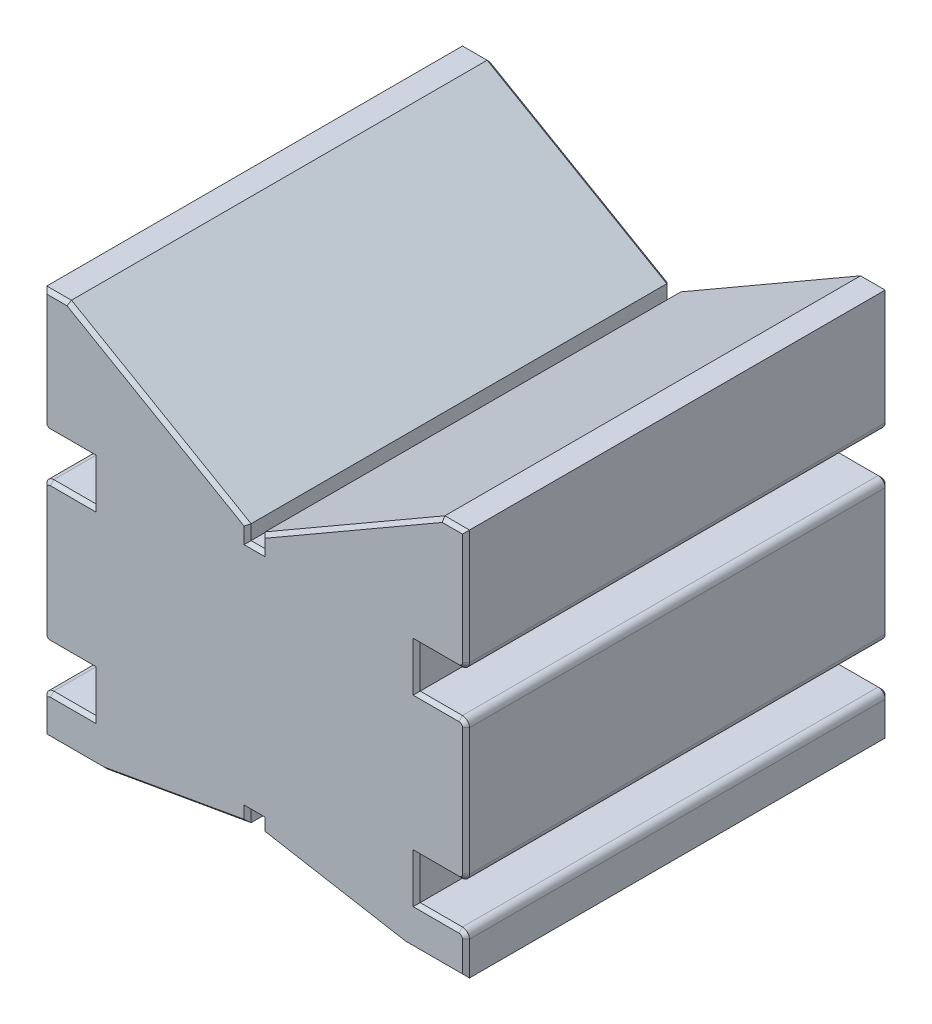
SolidWorks part; units mm, degrees
ref_plane "Front Plane" through (0, 0, 0) normal (0, 0, 1) x (1, 0, 0)
ref_plane "Top Plane" through (0, 0, 0) normal (0, 1, 0) x (1, 0, 0)
ref_plane "Right Plane" through (0, 0, 0) normal (1, 0, 0) x (0, 0, -1)
sketch "Sketch1" plane through (0, 0, 0) normal (0, 0, 1) x (1, 0, 0)
  line L0 (0, 25) -> (0, -25) construction
  line L1 (-23.3909, 0) -> (23.3909, 0) construction
  line L2 (-30, 0) -> (-30, 3)
  line L3 (-29, 4) -> (-23, 4)
  line L4 (-23, 4) -> (-23, 10)
  line L5 (-23, 10) -> (-29, 10)
  line L6 (-30, 11) -> (-30, 27.2998)
  line L7 (-30, 27.2998) -> (-26.5, 27.2998)
  line L8 (-26.5, 27.2998) -> (0, 12)
  line L9 (-30, 0) -> (-30, -15)
  line L10 (-29, -16) -> (-23, -16)
  line L11 (-23, -16) -> (-23, -22)
  line L12 (-23, -22) -> (-29, -22)
  line L13 (-30, -23) -> (-30, -27.7673)
  line L14 (-30, -27.7673) -> (-21.3656, -27.7673)
  line L15 (-21.3656, -27.7673) -> (0, -24)
  line L16 (21.3656, -27.7673) -> (0, -24)
  line L17 (30, -27.7673) -> (21.3656, -27.7673)
  line L18 (30, -23) -> (30, -27.7673)
  line L19 (23, -22) -> (29, -22)
  line L20 (23, -16) -> (23, -22)
  line L21 (29, -16) -> (23, -16)
  line L22 (30, 0) -> (30, -15)
  line L23 (26.5, 27.2998) -> (0, 12)
  line L24 (30, 27.2998) -> (26.5, 27.2998)
  line L25 (30, 11) -> (30, 27.2998)
  line L26 (23, 10) -> (29, 10)
  line L27 (23, 4) -> (23, 10)
  line L28 (29, 4) -> (23, 4)
  line L29 (30, 0) -> (30, 3)
  arc A0 (-30, -23) -> (-29, -22) centre (-29, -23) cw
  arc A1 (-30, -15) -> (-29, -16) centre (-29, -15) ccw
  arc A2 (-30, 3) -> (-29, 4) centre (-29, 3) cw
  arc A3 (-29, 10) -> (-30, 11) centre (-29, 11) cw
  arc A4 (30, -23) -> (29, -22) centre (29, -23) ccw
  arc A5 (29, -16) -> (30, -15) centre (29, -15) ccw
  arc A6 (30, 3) -> (29, 4) centre (29, 3) ccw
  arc A7 (29, 10) -> (30, 11) centre (29, 11) ccw
  point P36 (-30, -22)
  point P39 (-30, -16)
  point P42 (-30, 4)
  point P45 (-30, 10)
  point P48 (30, -22)
  point P51 (30, -16)
  point P54 (30, 4)
  point P57 (30, 10)
  dimension "D10" = 1
  dimension "D11" = 1
  dimension "D1" = 3.5
  dimension "D2" = 160
  dimension "D3" = 16
  dimension "D4" = 4
  dimension "D5" = 120
  dimension "D6" = 7
  dimension "D7" = 6
  dimension "D8" = 6
  dimension "D9" = 60
  dimension "D12" = 8
  dimension "D13" = 8
extrude "Boss-Extrude1" add sketch "Sketch1" along normal blind 60
sketch "Sketch3" plane through (0, 0, 0) normal (0, 0, -1) x (-1, 0, 0)
  line L1 (1, 10.5) -> (-1, 10.5)
  line L2 (1, 10.5) -> (1, 13.5)
  line L3 (1, 13.5) -> (-1, 13.5)
  line L4 (-1, 10.5) -> (-1, 13.5)
  line L5 (1, 10.5) -> (-1, 13.5) construction
  line L6 (1, 13.5) -> (-1, 10.5) construction
  line L7 (-1, -25.5) -> (1, -25.5)
  line L8 (-1, -25.5) -> (-1, -22.5)
  line L9 (-1, -22.5) -> (1, -22.5)
  line L10 (1, -25.5) -> (1, -22.5)
  line L11 (-1, -25.5) -> (1, -22.5) construction
  line L12 (-1, -22.5) -> (1, -25.5) construction
  point P0 (0, 12)
  point P6 (0, -24)
  dimension "D1" = 2
  dimension "D2" = 3
  dimension "D3" = 3
  dimension "D4" = 2
extrude "Cut-Extrude1" cut sketch "Sketch3" against normal through all
sketch "Sketch2" plane through (0, 0, 60) normal (0, 0, 1) x (1, 0, 0)
  line L0 (-33.9396, 80) -> (30, 80) construction
  line L1 (-29, 10) -> (-23, 10) construction
  line L2 (-30, -92) -> (29.6871, -92) construction
  line L3 (-23, -22) -> (-29, -22) construction
  point P4 (-26, 10)
  dimension "D1" = 70
  dimension "D2" = 70
chamfer "Chamfer1" distance 0.5 angle 45 80 edges at (-29.7071, 3.7071, 60) (-26, 4, 60) (-23, 7, 60) (-26, 10, 60) (-29.7071, 10.2929, 60) (-30, 19.1499, 60) (-28.25, 27.2998, 60) (-13.75, 19.9386, 60) (13.75, 19.9386, 60) (28.25, 27.2998, 60) (30, 19.1499, 60) (29.7071, 10.2929, 60) (26, 10, 60) (23, 7, 60) (26, 4, 60) (29.7071, 3.7071, 60) (30, -6, 60) (29.7071, -15.7071, 60) (26, -16, 60) (23, -19, 60) (26, -22, 60) (29.7071, -22.2929, 60) (30, -25.3837, 60) (25.6828, -27.7673, 60) (11.1828, -25.9718, 60) (-11.1828, -25.9718, 60) (-25.6828, -27.7673, 60) (-30, -25.3837, 60) (-29.7071, -22.2929, 60) (-26, -22, 60) (-23, -19, 60) (-26, -16, 60) (-29.7071, -15.7071, 60) (-30, -6, 60) (-26, -16, 0) (-23, -19, 0) (-26, -22, 0) (-29.7071, -22.2929, 0) (-30, -25.3837, 0) (-25.6828, -27.7673, 0) (-11.1828, -25.9718, 0) (11.1828, -25.9718, 0) (25.6828, -27.7673, 0) (30, -25.3837, 0) (29.7071, -22.2929, 0) (26, -22, 0) (23, -19, 0) (26, -16, 0) (29.7071, -15.7071, 0) (30, -6, 0) (29.7071, 3.7071, 0) (26, 4, 0) (23, 7, 0) (26, 10, 0) (29.7071, 10.2929, 0) (30, 19.1499, 0) (28.25, 27.2998, 0) (13.75, 19.9386, 0) (-13.75, 19.9386, 0) (-28.25, 27.2998, 0) (-30, 19.1499, 0) (-29.7071, 10.2929, 0) (-26, 10, 0) (-23, 7, 0) (-26, 4, 0) (-29.7071, 3.7071, 0) (-30, -6, 0) (-29.7071, -15.7071, 0) (1, -23.3382, 60) (0, -22.5, 60) (-1, -23.3382, 60) (-1, 11.5387, 60) (0, 10.5, 60) (1, 11.5387, 60) (-1, 11.5387, 0) (-1, -23.3382, 0) (0, -22.5, 0) (1, -23.3382, 0) (1, 11.5387, 0) (0, 10.5, 0)
